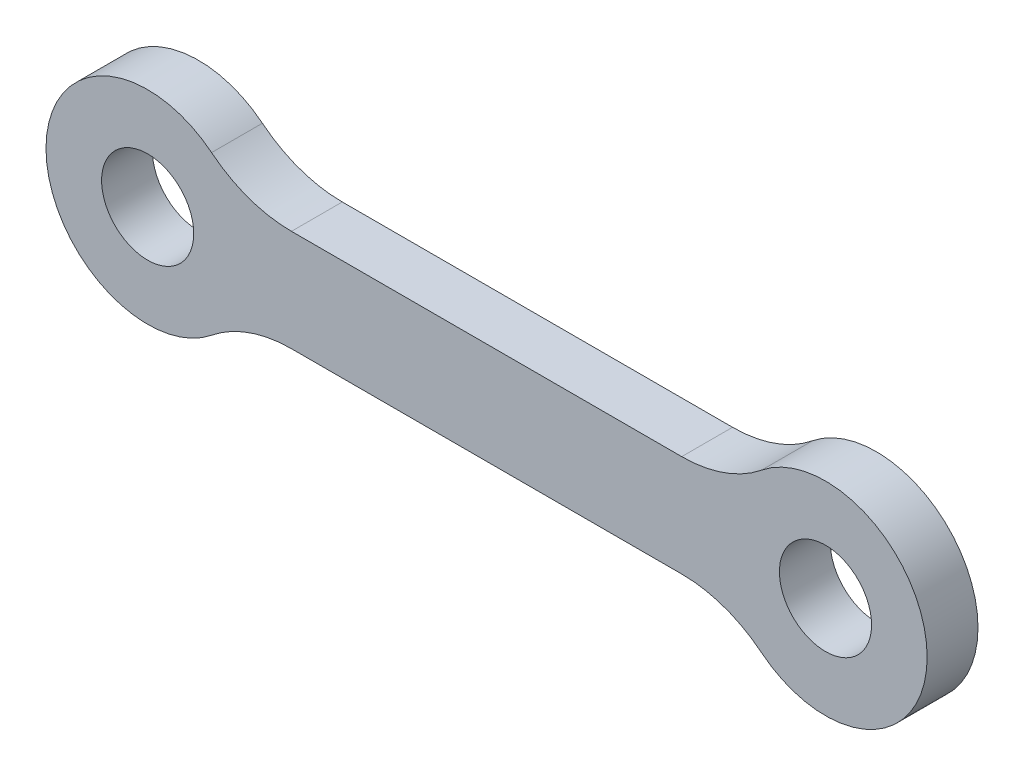
SolidWorks part; units mm, degrees
ref_plane "Front Plane" through (0, 0, 0) normal (0, 0, 1) x (1, 0, 0)
ref_plane "Top Plane" through (0, 0, 0) normal (0, 1, 0) x (1, 0, 0)
ref_plane "Right Plane" through (0, 0, 0) normal (1, 0, 0) x (0, 0, -1)
sketch "Sketch1" plane through (0, 0, 0) normal (0, 0, 1) x (1, 0, 0)
  line L0 (-26.2008, 0) -> (90.0531, 0) construction
  line L1 (14.3684, 5.08) -> (53.3649, 5.08)
  line L2 (14.3684, -5.08) -> (53.3649, -5.08)
  circle A0 centre (0, 0) radius 4.6037
  arc A1 (6.386, 7.9022) -> (6.386, -7.9022) centre (0, 0) ccw
  circle A2 centre (67.7333, 0) radius 4.6038
  arc A3 (61.3474, -7.9022) -> (61.3474, 7.9022) centre (67.7333, 0) ccw
  arc A4 (61.3474, 7.9022) -> (53.3649, 5.08) centre (53.3649, 17.78) cw
  arc A5 (53.3649, -5.08) -> (61.3474, -7.9022) centre (53.3649, -17.78) cw
  arc A6 (14.3684, -5.08) -> (6.386, -7.9022) centre (14.3684, -17.78) ccw
  arc A7 (14.3684, 5.08) -> (6.386, 7.9022) centre (14.3684, 17.78) cw
  point P14 (58.9345, 5.08)
  point P17 (58.9345, -5.08)
  point P20 (8.7988, -5.08)
  point P23 (8.7988, 5.08)
  dimension "D1" = 9.2075
  dimension "D2" = 20.32
  dimension "D3" = 20.32
  dimension "D4" = 9.2075
  dimension "D7" = 12.7
  dimension "D5" = 67.7333
  dimension "D6" = 5.08
extrude "Boss-Extrude1" add sketch "Sketch1" along normal blind 5.08
